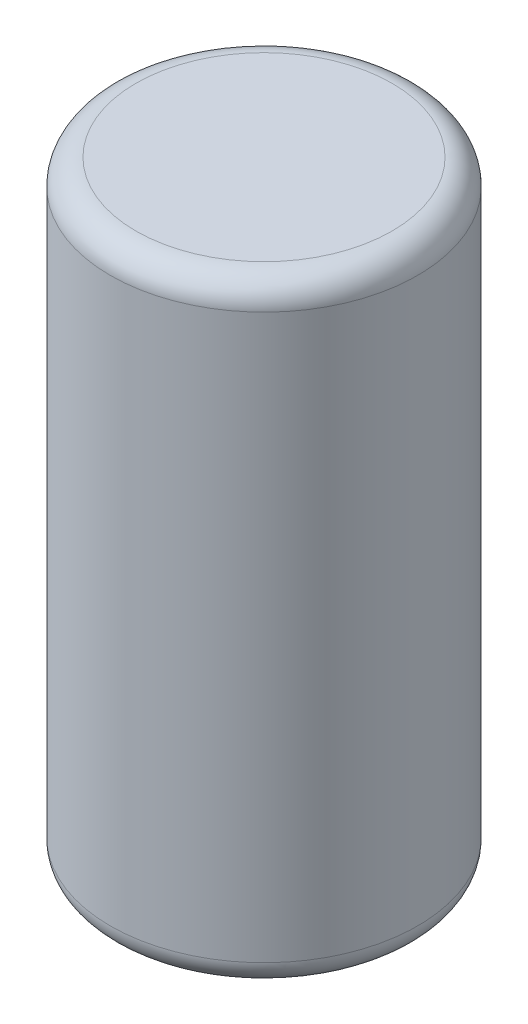
SolidWorks part; units mm, degrees
ref_plane "Front Plane" through (0, 0, 0) normal (0, 0, 1) x (1, 0, 0)
ref_plane "Top Plane" through (0, 0, 0) normal (0, 1, 0) x (1, 0, 0)
ref_plane "Right Plane" through (0, 0, 0) normal (1, 0, 0) x (0, 0, -1)
sketch "Sketch1" plane through (0, 0, 0) normal (0, 0, 1) x (1, 0, 0)
  line L0 (0, 6) -> (0, -6)
  line L1 (0, -6) -> (2.5, -6)
  line L2 (3, -5.5) -> (3, 5.5)
  line L3 (2.5, 6) -> (0, 6)
  arc A0 (2.5, -6) -> (3, -5.5) centre (2.5, -5.5) ccw
  arc A1 (3, 5.5) -> (2.5, 6) centre (2.5, 5.5) ccw
  point P3 (0, 0)
  point P8 (3, -6)
  point P11 (3, 6)
  dimension "D3" = 0.5
  dimension "D1" = 3
  dimension "D2" = 12
revolve "Revolve1" add sketch "Sketch1" angle 360 about L0
